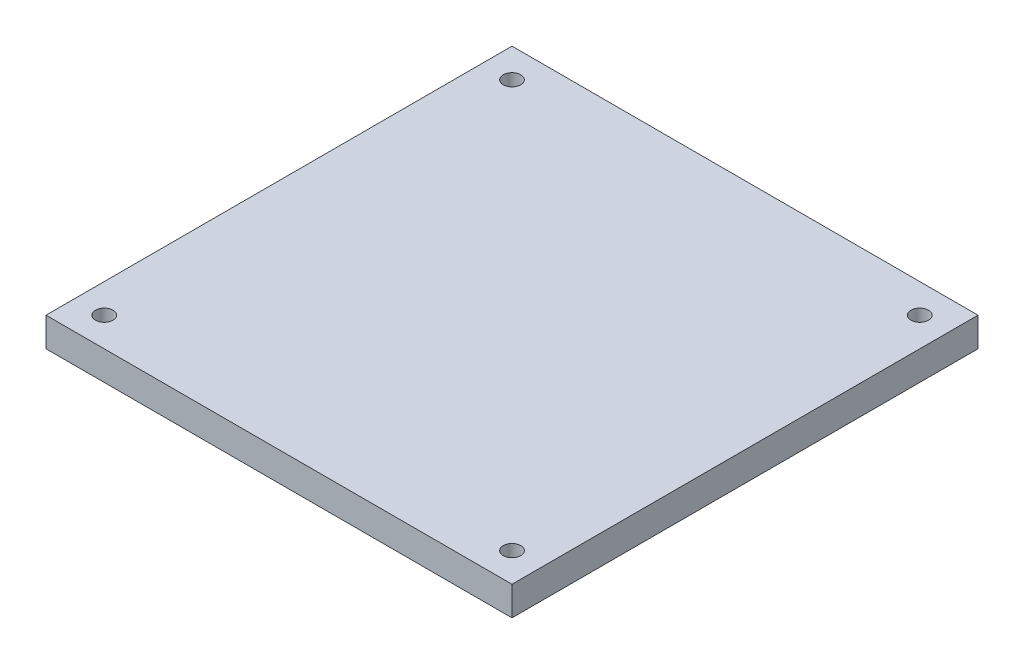
SolidWorks part; units mm, degrees
material "ABS PC"
ref_plane "Plan de face" through (0, 0, 0) normal (0, 0, 1) x (1, 0, 0)
ref_plane "Plan de dessus" through (0, 0, 0) normal (0, 1, 0) x (1, 0, 0)
ref_plane "Plan de droite" through (0, 0, 0) normal (1, 0, 0) x (0, 0, -1)
sketch "Esquisse1" plane through (0, 0, 0) normal (0, 1, 0) x (1, 0, 0)
  line L0 (-40, 40) -> (40, -40) construction
  line L1 (-40, 40) -> (40, 40)
  line L2 (-40, 40) -> (-40, -40)
  line L3 (-40, -40) -> (40, -40)
  line L4 (40, 40) -> (40, -40)
  dimension "D1" = 80
extrude "Boss.-Extru.1" add sketch "Esquisse1" along normal blind 5
sketch "Esquisse2" plane through (0, 5, 0) normal (0, 1, 0) x (1, 0, 0)
  line L0 (35, -35) -> (-35, 35) construction
  line L1 (-40, 40) -> (-40, -40) construction
  circle A0 centre (-35, 35) radius 1.5
  circle A1 centre (35, -35) radius 1.5
  circle A2 centre (-35, -35) radius 1.5
  circle A3 centre (35, 35) radius 1.5
  dimension "D2" = 3
  dimension "D3" = 3
  dimension "D4" = 3
  dimension "D1" = 5
extrude "Enlèv. mat.-Extru.1" cut sketch "Esquisse2" against normal through all
